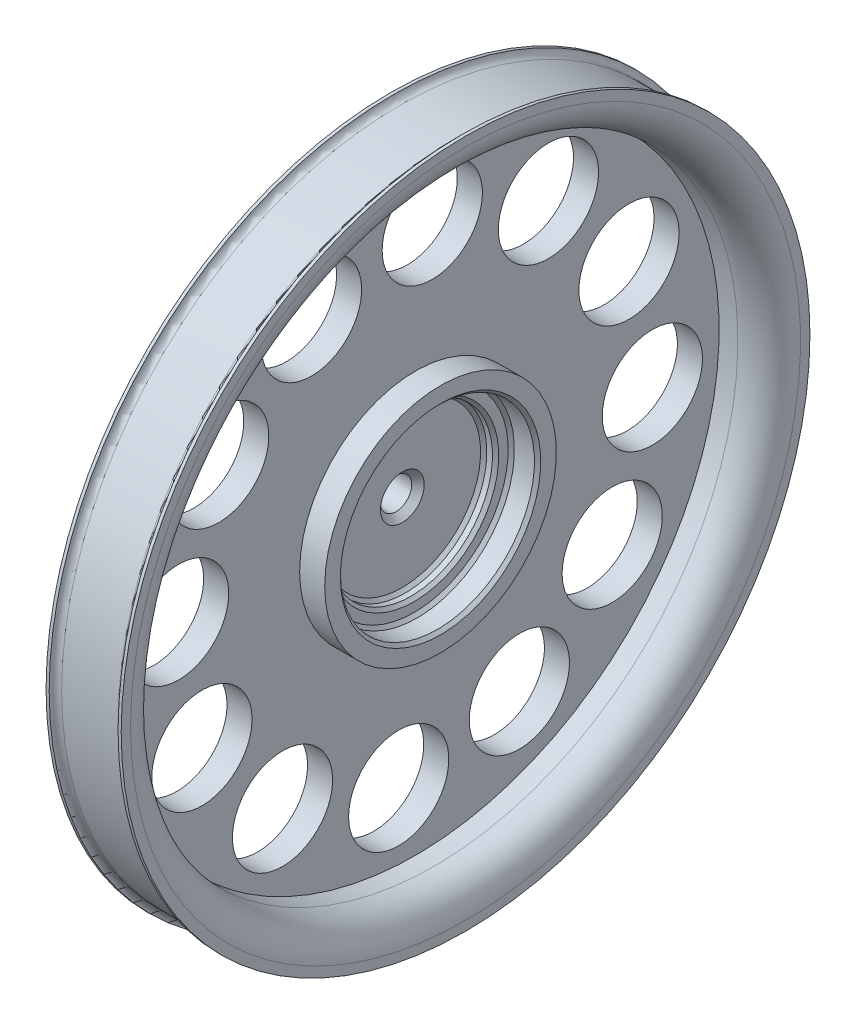
SolidWorks part; units mm, degrees
ref_plane "Płaszczyzna przednia" through (0, 0, 0) normal (0, 0, 1) x (1, 0, 0)
ref_plane "Płaszczyzna górna" through (0, 0, 0) normal (0, 1, 0) x (1, 0, 0)
ref_plane "Płaszczyzna prawa" through (0, 0, 0) normal (1, 0, 0) x (0, 0, -1)
sketch "Szkic1" plane through (0, 0, 0) normal (0, 0, 1) x (1, 0, 0)
  line L0 (0, 27.5782) -> (0, 21.0782)
  line L2 (-12, 27.5782) -> (-12, -3.9924)
  line L6 (0, 21.0782) -> (-8, 21.0782)
  line L8 (-4, -11.9218) -> (-8.2, -11.9218)
  line L11 (-20.1, -27.4218) -> (-10.1, -27.4218)
  line L12 (-10.1, -27.4218) -> (-10.1, -14.4218)
  line L13 (-10.1, -14.4218) -> (-8.2, -14.4218)
  line L14 (-8.2, -14.4218) -> (-8.2, -11.9218)
  line L15 (-8, 21.0782) -> (-8, -8.9218)
  line L16 (-8, -8.9218) -> (-4, -8.9218)
  line L17 (-4, -8.9218) -> (-4, -11.9218)
  line L19 (-12, -3.9924) -> (-20.1, -14.4218)
  line L20 (-20.1, -14.4218) -> (-20.1, -27.4218)
  line L21 (-12, 27.5782) -> (-11.5, 27.5782)
  line L22 (0, 27.5782) -> (-0.5, 27.5782)
  line L23 (-10.5049, 26.581) -> (-1.499, 26.581)
  arc A0 (-11.5, 27.5782) -> (-10.5049, 26.581) centre (-10.5, 27.581) ccw
  arc A1 (-0.5, 27.5782) -> (-1.499, 26.581) centre (-1.5, 27.581) cw
  dimension "D8" = 1
  dimension "D9" = 1
  dimension "D1" = 13
  dimension "D2" = 2.5
  dimension "D3" = 1.9
  dimension "D4" = 4.2
  dimension "D5" = 4
  dimension "D6" = 30
  dimension "D7" = 3
  dimension "D10" = 8
  dimension "D11" = 10
  dimension "D12" = 0.5
  dimension "D13" = 0.5
  dimension "D14" = 12
  dimension "D15" = 55
revolve "Obrót1" add sketch "Szkic1" angle 360 about L11
sketch "Szkic2" plane through (-20.1, 0, 0) normal (-1, 0, 0) x (0, 0, 1)
  circle A0 centre (0, -27.4218) radius 2.5
  dimension "D1" = 5
extrude "Wytnij-wyciągnięcie1" cut sketch "Szkic2" against normal through all
fillet "Zaokrąglenie1" radius 10 2 edges at (-12, -27.4218, 23.4293) (-20.1, -27.4218, 13)
fillet "Zaokrąglenie2" radius 5 1 edges at (0, -27.4218, 48.5)
chamfer "Sfazowanie1" distance 1 angle 45 2 edges at (-10.1, -27.4218, 2.5) (-20.1, -27.4218, 2.5)
chamfer "Sfazowanie2" distance 0.5 angle 45 2 edges at (-10.1, -27.4218, 13) (-8.2, -27.4218, 13)
chamfer "Sfazowanie3" distance 0.5 angle 45 2 edges at (-8.2, -27.4218, 15.5) (-4, -27.4218, 15.5)
sketch "Szkic3" plane through (-12, 0, 0) normal (-1, 0, 0) x (0, 0, 1)
  circle A0 centre (37.8293, -24.7415) radius 8
  circle A1 centre (34.1013, -44.0153) radius 8
  circle A2 centre (21.2358, -58.8428) radius 8
  circle A3 centre (2.6802, -65.2511) radius 8
  circle A4 centre (-16.5935, -61.523) radius 8
  circle A5 centre (-31.4211, -48.6576) radius 8
  circle A6 centre (-37.8293, -30.102) radius 8
  circle A7 centre (-34.1013, -10.8282) radius 8
  circle A8 centre (-21.2358, 3.9993) radius 8
  circle A9 centre (-2.6802, 10.4076) radius 8
  circle A10 centre (16.5935, 6.6795) radius 8
  circle A11 centre (31.4211, -6.1859) radius 8
  point P2 (0, 0)
  point P3 (35.7852, -24.9337)
  point P27 (0, -27.4218)
  dimension "D1" = 16
  dimension "D2" = 12
extrude "Wytnij-wyciągnięcie2" cut sketch "Szkic3" against normal through all
